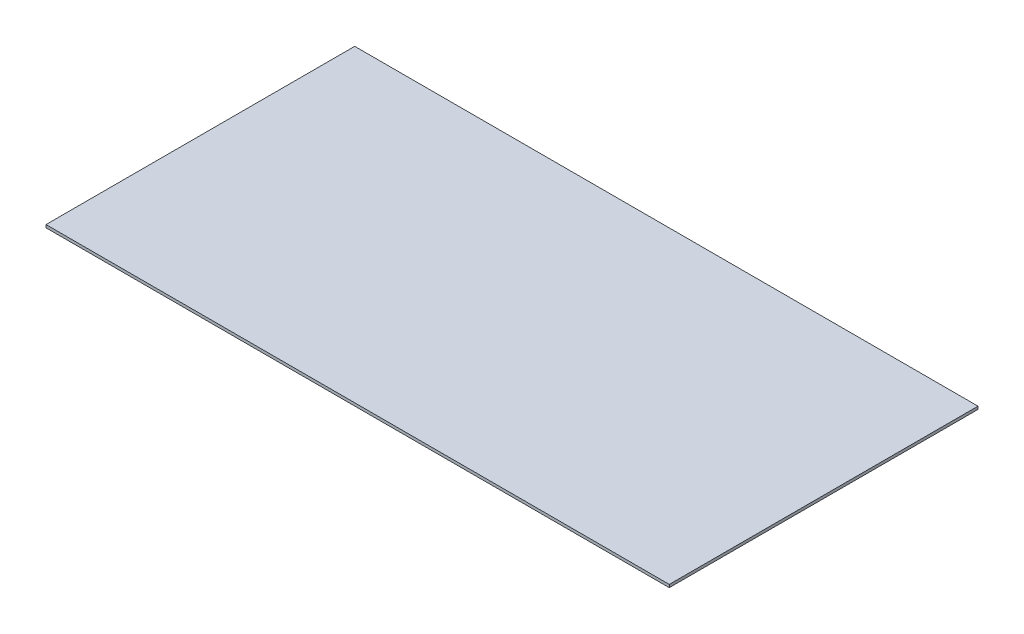
SolidWorks part; units mm, degrees
material "Teak"
ref_plane "Front Plane" through (0, 0, 0) normal (0, 0, 1) x (1, 0, 0)
ref_plane "Top Plane" through (0, 0, 0) normal (0, 1, 0) x (1, 0, 0)
ref_plane "Right Plane" through (0, 0, 0) normal (1, 0, 0) x (0, 0, -1)
sketch "Sketch1" plane through (0, 0, 0) normal (0, 1, 0) x (1, 0, 0)
  line L1 (-609.6, -301.9425) -> (609.6, -301.9425)
  line L2 (-609.6, -301.9425) -> (-609.6, 301.9425)
  line L3 (-609.6, 301.9425) -> (609.6, 301.9425)
  line L4 (609.6, -301.9425) -> (609.6, 301.9425)
  line L5 (-609.6, -301.9425) -> (609.6, 301.9425) construction
  line L6 (-609.6, 301.9425) -> (609.6, -301.9425) construction
  point P0 (0, 0)
  dimension "D1" = 1219.2
  dimension "D2" = 603.885
extrude "Boss-Extrude1" add sketch "Sketch1" along normal blind 5.5562
